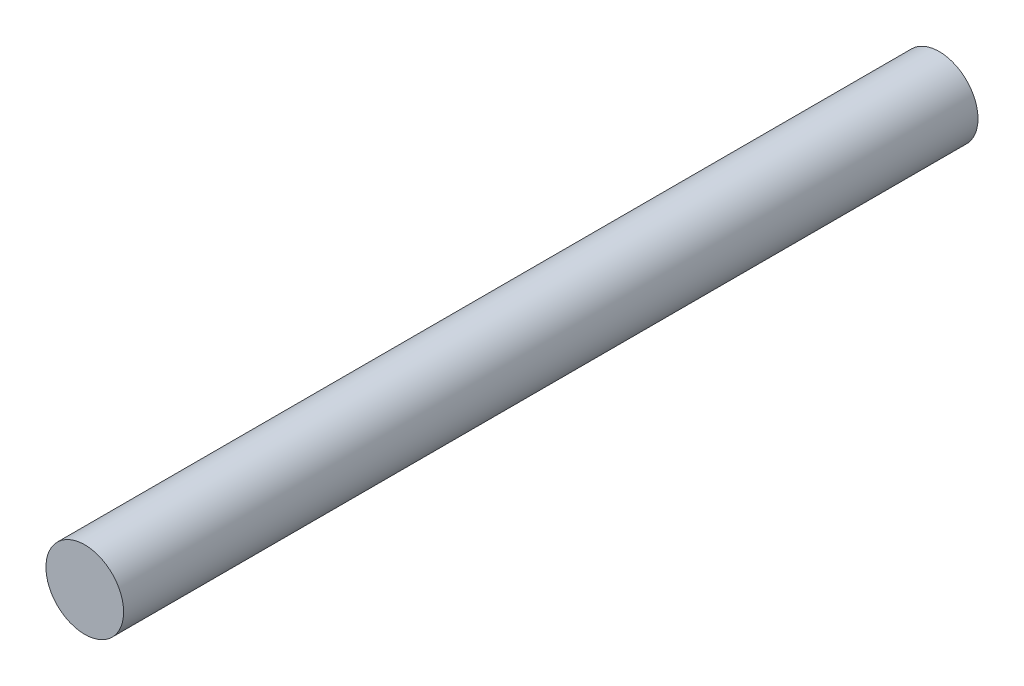
SolidWorks part; units mm, degrees
ref_plane "Front Plane" through (0, 0, 0) normal (0, 0, 1) x (1, 0, 0)
ref_plane "Top Plane" through (0, 0, 0) normal (0, 1, 0) x (1, 0, 0)
ref_plane "Right Plane" through (0, 0, 0) normal (1, 0, 0) x (0, 0, -1)
sketch "Sketch1" plane through (0, 0, 0) normal (0, 0, 1) x (1, 0, 0)
  circle A0 centre (0, 0) radius 2.5
  dimension "D1" = 5
extrude "Boss-Extrude1" add sketch "Sketch1" along normal blind 55
